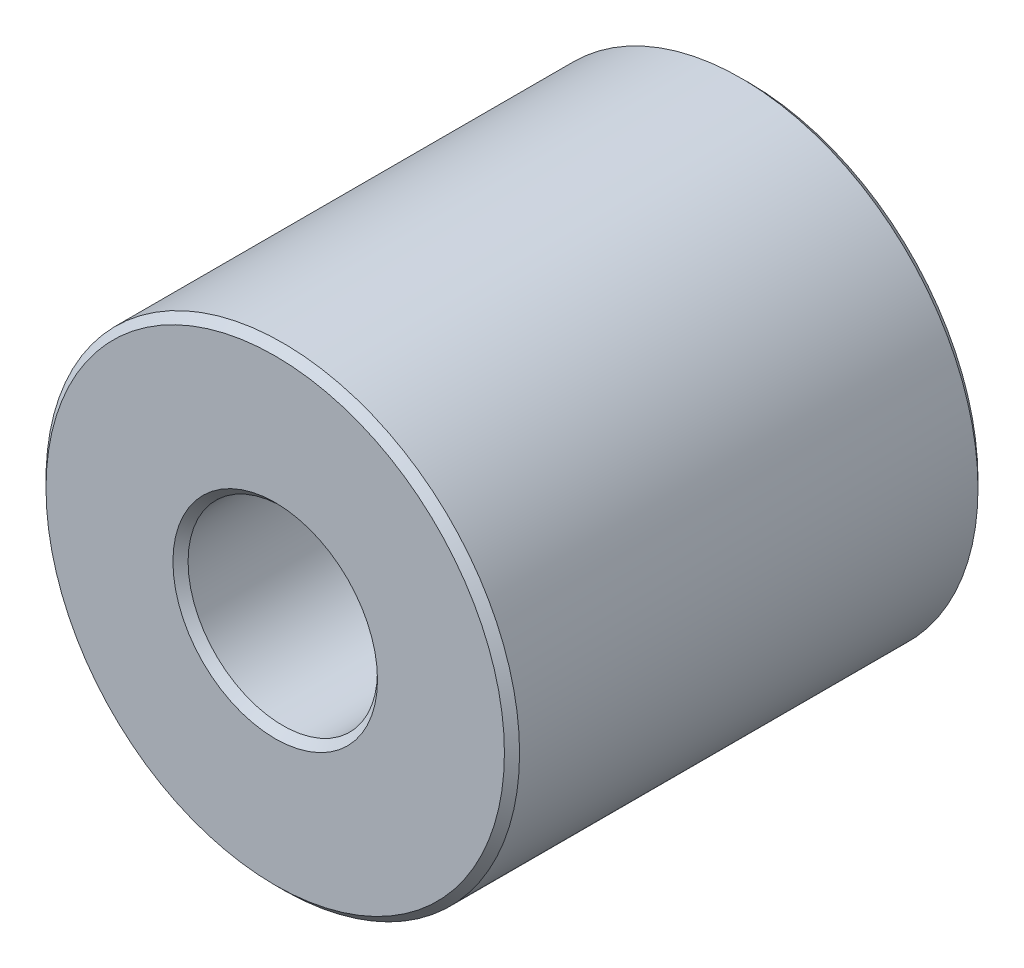
SolidWorks part; units mm, degrees
material "AISI 4130 Steel, normalized at 870C"
ref_plane "Front Plane" through (0, 0, 0) normal (0, 0, 1) x (1, 0, 0)
ref_plane "Top Plane" through (0, 0, 0) normal (0, 1, 0) x (1, 0, 0)
ref_plane "Right Plane" through (0, 0, 0) normal (1, 0, 0) x (0, 0, -1)
sketch "Sketch1" plane through (0, 0, 0) normal (0, 0, 1) x (1, 0, 0)
  circle A0 centre (0, 0) radius 3.175
  circle A1 centre (0, 0) radius 7.9375
  dimension "D1" = 6.35
  dimension "D2" = 15.875
extrude "Boss-Extrude1" add sketch "Sketch1" along normal blind 15.875
chamfer "Chamfer1" distance 0.254 angle 45 4 edges at (7.9375, 0, 0) (3.175, 0, 0) (7.9375, 0, 15.875) (3.175, 0, 15.875)
